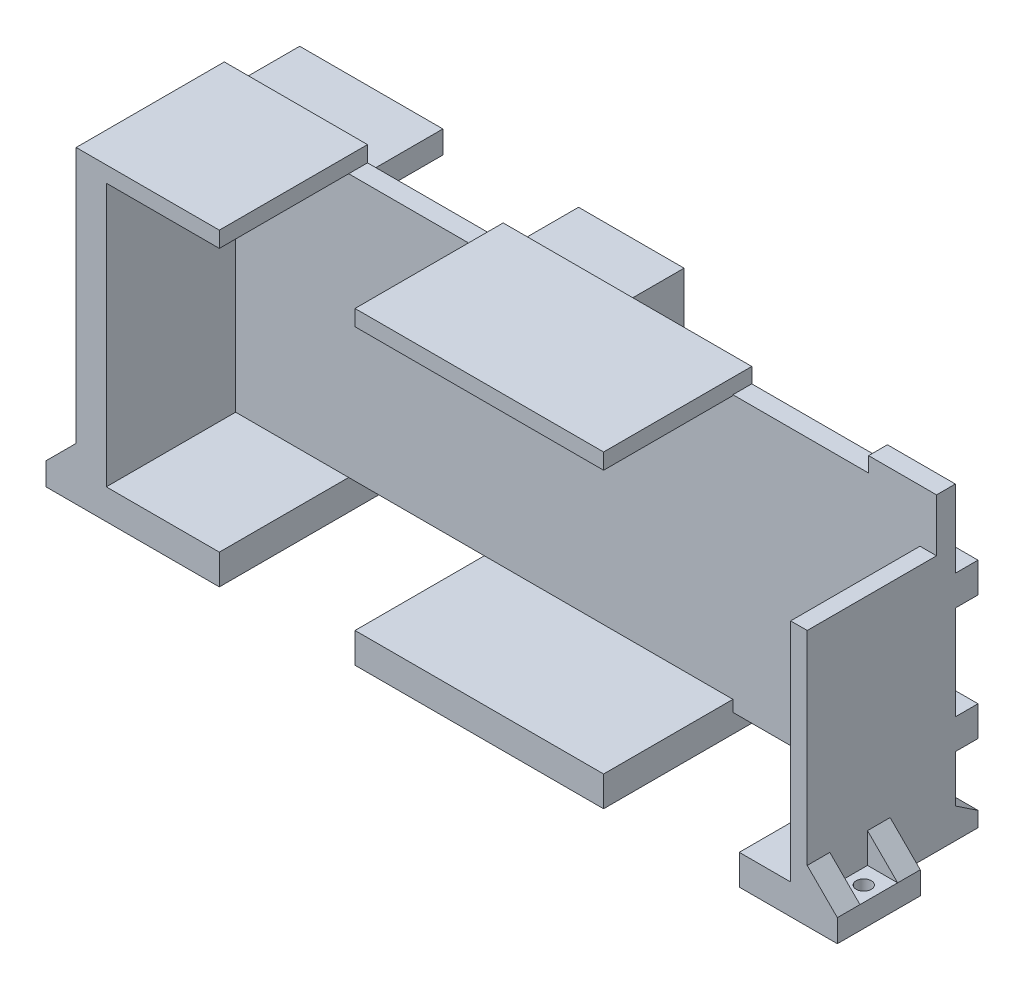
SolidWorks part; units mm, degrees
material "ABS"
ref_plane "Front Plane" through (0, 0, 0) normal (0, 0, 1) x (1, 0, 0)
ref_plane "Top Plane" through (0, 0, 0) normal (0, 1, 0) x (1, 0, 0)
ref_plane "Right Plane" through (0, 0, 0) normal (1, 0, 0) x (0, 0, -1)
sketch "Sketch1" plane through (0, 0, 0) normal (0, 0, 1) x (1, 0, 0)
  line L1 (29.337, -20.193) -> (-29.337, -20.193)
  line L2 (29.337, -20.193) -> (29.337, 20.193)
  line L3 (29.337, 20.193) -> (-29.337, 20.193)
  line L4 (-29.337, -20.193) -> (-29.337, 20.193)
  line L5 (29.337, -20.193) -> (-29.337, 20.193) construction
  line L6 (29.337, 20.193) -> (-29.337, -20.193) construction
  line L7 (32.385, 24.003) -> (-32.385, 24.003)
  line L8 (32.385, 24.003) -> (32.385, -24.003)
  line L9 (32.385, -24.003) -> (-32.385, -24.003)
  line L10 (-32.385, 24.003) -> (-32.385, -24.003)
  line L11 (32.385, 24.003) -> (-32.385, -24.003) construction
  line L12 (32.385, -24.003) -> (-32.385, 24.003) construction
  point P0 (0, 0)
  point P6 (0, 0)
  dimension "D1" = 40.386
  dimension "D2" = 58.674
  dimension "D3" = 3.048
  dimension "D4" = 3.81
  dimension "D5" = 3.81
extrude "Boss-Extrude1" add sketch "Sketch1" along normal blind 12.7
sketch "Sketch3" plane through (0, 0, 12.7) normal (0, 0, 1) x (1, 0, 0)
  line L0 (79.354, -24.003) -> (79.354, -20.828)
  line L1 (-32.385, -24.003) -> (56.494, -24.003)
  line L2 (-32.385, -24.003) -> (-32.385, 28.067)
  line L3 (-32.385, 28.067) -> (56.494, 28.067)
  line L4 (90.805, -24.003) -> (90.805, 28.067)
  line L5 (79.354, -20.828) -> (56.494, -20.828)
  line L6 (56.494, -20.828) -> (56.494, -24.003)
  line L7 (79.354, -24.003) -> (90.805, -24.003)
  line L8 (79.354, 28.067) -> (79.354, 25.527)
  line L9 (79.354, 25.527) -> (56.494, 25.527)
  line L10 (56.494, 25.527) -> (56.494, 28.067)
  line L11 (79.354, 28.067) -> (90.805, 28.067)
  dimension "D1" = 123.19
  dimension "D2" = 52.07
  dimension "D3" = 3.175
  dimension "D4" = 22.86
  dimension "D5" = 11.451
  dimension "D6" = 22.86
  dimension "D7" = 2.54
extrude "Boss-Extrude2" add sketch "Sketch3" along normal blind 3.175
sketch "Sketch5" plane through (0, 0, 15.875) normal (0, 0, 1) x (1, 0, 0)
  line L0 (-32.385, 28.067) -> (-32.385, -24.003)
  line L1 (-32.385, -24.003) -> (56.494, -24.003)
  line L2 (56.494, -24.003) -> (56.494, -18.923)
  line L3 (56.494, -18.923) -> (79.354, -18.923)
  line L4 (79.354, -18.923) -> (79.354, -24.003)
  line L5 (79.354, -24.003) -> (90.805, -24.003)
  line L6 (90.805, -24.003) -> (90.805, 19.177)
  line L7 (90.805, 28.067) -> (79.354, 28.067) construction
  line L9 (88.011, -18.923) -> (79.354, -18.923)
  line L10 (56.494, 25.4) -> (56.494, 28.067)
  line L11 (56.494, 28.067) -> (-32.385, 28.067)
  line L12 (-27.305, 25.4) -> (-27.305, -18.923)
  line L13 (-27.305, -18.923) -> (56.494, -18.923)
  line L14 (79.354, -24.003) -> (79.354, -18.923)
  line L15 (88.011, -18.923) -> (88.011, 19.177)
  line L17 (56.494, 25.4) -> (-27.305, 25.4)
  line L18 (88.011, 19.177) -> (90.805, 19.177)
  line M7 (-32.385, 28.067) -> (-32.385, -24.003)
  line M8 (-32.385, -24.003) -> (56.494, -24.003)
  line M9 (56.494, -24.003) -> (56.494, -20.828)
  line M11 (79.354, -20.828) -> (79.354, -24.003)
  line M12 (79.354, -24.003) -> (90.805, -24.003)
  line M13 (90.805, -24.003) -> (90.805, 28.067)
  line M17 (56.494, 25.527) -> (56.494, 28.067)
  line M18 (56.494, 28.067) -> (-32.385, 28.067)
  dimension "D1" = 5.08
  dimension "D2" = 2.794
  dimension "D3" = 2.667
  dimension "D4" = 5.08
  dimension "D5" = 8.89
extrude "Boss-Extrude3" add sketch "Sketch5" along normal blind 21.7932 contours L17 L10 L13 L12 M17 M18 M7 M8 M9 | L18 L15 L9 M11 M12 M13
sketch "Sketch6" plane through (0, 0, 37.6682) normal (0, 0, 1) x (1, 0, 0)
  line L1 (-8.255, 28.067) -> (14.605, 28.067)
  line L2 (-8.255, 28.067) -> (-8.255, 25.4)
  line L3 (-8.255, 25.4) -> (14.605, 25.4)
  line L4 (14.605, 28.067) -> (14.605, 25.4)
  line L9 (-8.255, -24.003) -> (-8.255, -18.923)
  line L12 (-8.255, -18.923) -> (14.605, -18.923)
  line L13 (14.605, -18.923) -> (14.605, -24.003)
  line L14 (14.605, -24.003) -> (-8.255, -24.003)
  line L17 (56.494, 28.067) -> (-32.385, 28.067) construction
  line L18 (-32.385, 28.067) -> (-32.385, -24.003) construction
  line L20 (-32.385, -24.003) -> (56.494, -24.003) construction
  line L24 (56.494, 25.4) -> (-27.305, 25.4) construction
  line L25 (-27.305, -18.923) -> (56.494, -18.923) construction
  dimension "D1" = 22.86
  dimension "D2" = 24.13
extrude "Cut-Extrude1" cut sketch "Sketch6" against normal through all
sketch "Sketch7" plane through (0, 0, 0) normal (0, 0, -1) x (-1, 0, 0)
  line L0 (-32.385, 24.003) -> (32.385, 24.003) construction
  line L1 (-14.605, 24.003) -> (8.255, 24.003)
  line L2 (-14.605, 24.003) -> (-14.605, 20.193)
  line L3 (-14.605, 20.193) -> (8.255, 20.193)
  line L4 (8.255, 24.003) -> (8.255, 20.193)
  line L5 (-29.337, 20.193) -> (29.337, 20.193) construction
  line L6 (29.337, -20.193) -> (8.255, -20.193) construction
  line L7 (-14.605, -20.193) -> (8.255, -20.193)
  line L8 (-14.605, -20.193) -> (-14.605, -21.336)
  line L9 (-14.605, -21.336) -> (8.255, -21.336)
  line L10 (8.255, -20.193) -> (8.255, -21.336)
  line L11 (-14.605, -20.193) -> (-14.605, -24.003) construction
  line L14 (8.255, 28.067) -> (8.255, 24.003) construction
  line L15 (-14.605, 24.003) -> (-14.605, 28.067) construction
extrude "Cut-Extrude2" cut sketch "Sketch7" against normal blind 12.7
sketch "Sketch10" plane through (-32.385, 0, 0) normal (-1, 0, 0) x (0, 0, 1)
  line L0 (30.6832, -24.003) -> (30.6832, -21.2771) construction
  line L1 (37.6682, -24.003) -> (0, -24.003) construction
  line L2 (37.6682, 28.067) -> (37.6682, -24.003) construction
  line L3 (23.6982, -24.003) -> (37.6682, -24.003)
  line L4 (23.6982, -24.003) -> (23.6982, -20.193)
  line L5 (23.6982, -20.193) -> (37.6682, -20.193)
  line L6 (37.6682, -24.003) -> (37.6682, -20.193)
  dimension "D1" = 13.97
  dimension "D2" = 3.81
extrude "Boss-Extrude4" add sketch "Sketch10" along normal blind 5.08
sketch "Sketch11" plane through (0, 0, 37.6682) normal (0, 0, 1) x (1, 0, 0)
  line L0 (-37.465, -20.193) -> (-32.385, -20.193)
  line L1 (-32.385, -20.193) -> (-32.385, -15.113)
  line L3 (-32.385, -15.113) -> (-37.465, -20.193)
  line L4 (-32.385, 28.067) -> (-32.385, -24.003) construction
  dimension "D1" = 5.08
  dimension "D2" = 5.08
extrude "Boss-Extrude5" add sketch "Sketch11" against normal blind 3.81
sketch "Sketch12" plane through (0, -20.193, 0) normal (0, 1, 0) x (1, 0, 0)
  line L0 (-34.925, -23.6982) -> (-34.925, -37.6682) construction
  line L1 (-37.465, -23.6982) -> (-32.385, -23.6982) construction
  line L2 (-32.385, -37.6682) -> (-37.465, -37.6682) construction
  line L3 (-37.465, -30.6832) -> (-32.385, -30.6832) construction
  line L4 (-37.465, -33.8582) -> (-37.465, -23.6982) construction
  line L5 (-32.385, -37.6682) -> (-32.385, -12.7) construction
  circle A0 centre (-34.925, -30.6832) radius 1.27
  dimension "D1" = 2.54
extrude "Cut-Extrude3" cut sketch "Sketch12" against normal through all
sketch "Sketch13" plane through (0, 0, 23.6982) normal (0, 0, -1) x (-1, 0, 0)
  line L0 (32.385, -15.113) -> (32.385, -20.193)
  line L1 (32.385, -20.193) -> (37.465, -20.193)
  line L2 (37.465, -20.193) -> (32.385, -15.113)
extrude "Boss-Extrude7" add sketch "Sketch13" against normal blind 3.81
sketch "Sketch14" plane through (90.805, 0, 0) normal (1, 0, 0) x (0, 0, -1)
  line L0 (-37.6682, -24.003) -> (-37.6682, 19.177) construction
  line L1 (-37.6682, -24.003) -> (-12.7, -24.003) construction
  line L3 (-37.6682, -24.003) -> (-23.6982, -24.003)
  line L4 (-37.6682, -24.003) -> (-37.6682, -20.193)
  line L5 (-37.6682, -20.193) -> (-23.6982, -20.193)
  line L6 (-23.6982, -24.003) -> (-23.6982, -20.193)
  dimension "D1" = 13.97
  dimension "D2" = 3.81
extrude "Boss-Extrude8" add sketch "Sketch14" along normal blind 5.08
sketch "Sketch15" plane through (0, -20.193, 0) normal (0, 1, 0) x (1, 0, 0)
  line L0 (90.805, -30.6832) -> (95.885, -30.6832) construction
  line L1 (90.805, -23.6982) -> (90.805, -37.6682) construction
  line L2 (95.885, -23.6982) -> (95.885, -37.6682) construction
  line L3 (93.345, -37.6682) -> (93.345, -23.6982) construction
  line L4 (95.885, -37.6682) -> (90.805, -37.6682) construction
  line L5 (95.885, -23.6982) -> (90.805, -23.6982) construction
  circle A0 centre (93.345, -30.6832) radius 1.27
  circle A1 centre (-34.925, -30.6832) radius 1.27 construction
  dimension "D1" = 2.54
  dimension "D2" = 0
  dimension "D3" = 128.27
extrude "Cut-Extrude4" cut sketch "Sketch15" against normal through all
sketch "Sketch17" plane through (0, 0, 37.6682) normal (0, 0, 1) x (1, 0, 0)
  line L0 (95.885, -20.193) -> (90.805, -20.193)
  line L1 (90.805, -20.193) -> (90.805, -15.113)
  line L3 (90.805, -20.193) -> (90.805, 19.177) construction
  line L4 (90.805, -15.113) -> (95.885, -20.193)
extrude "Boss-Extrude9" add sketch "Sketch17" against normal blind 3.81
sketch "Sketch18" plane through (0, 0, 23.6982) normal (0, 0, -1) x (-1, 0, 0)
  line L0 (-95.885, -20.193) -> (-90.805, -20.193)
  line L1 (-90.805, -20.193) -> (-90.805, -15.113)
  line L2 (-90.805, -15.113) -> (-95.885, -20.193)
extrude "Boss-Extrude10" add sketch "Sketch18" against normal blind 3.81
sketch "Sketch19" plane through (0, 28.067, 0) normal (0, 1, 0) x (1, 0, 0)
  line L1 (90.805, -12.7) -> (86.995, -12.7)
  line L2 (90.805, -12.7) -> (90.805, -8.89)
  line L3 (90.805, -8.89) -> (86.995, -8.89)
  line L4 (86.995, -12.7) -> (86.995, -8.89)
  dimension "D1" = 3.81
  dimension "D2" = 3.81
extrude "Boss-Extrude11" [suppressed] add sketch "Sketch19" against normal up to surface (52.07 mm away)
sketch "Sketch20" [suppressed] plane through (0, 0, 12.7) normal (0, 0, -1) x (-1, 0, 0)
  line L0 (-67.924, -20.828) -> (-67.924, 25.527) construction
  line L1 (-56.494, -20.828) -> (-79.354, -20.828) construction
  line L2 (-79.354, 25.527) -> (-56.494, 25.527) construction
  line L3 (-32.385, -24.003) -> (-32.385, 24.003) construction
  line L4 (-32.385, -8.128) -> (-86.995, -8.128)
  line L5 (-32.385, -8.128) -> (-32.385, -11.938)
  line L6 (-32.385, -11.938) -> (-86.995, -11.938)
  line L7 (-86.995, -8.128) -> (-86.995, -11.938)
  line L8 (-86.995, -24.003) -> (-86.995, 28.067) construction
  line L9 (-86.995, -24.003) -> (-86.995, 28.067) construction
  line L10 (-32.385, 16.637) -> (-86.995, 16.637)
  line L11 (-32.385, 16.637) -> (-32.385, 12.827)
  line L12 (-32.385, 12.827) -> (-86.995, 12.827)
  line L13 (-86.995, 16.637) -> (-86.995, 12.827)
  dimension "D1" = 54.61
  dimension "D2" = 3.81
  dimension "D3" = 3.81
  dimension "D4" = 54.61
  dimension "D5" = 8.89
  dimension "D6" = 8.89
extrude "Boss-Extrude12" [suppressed] add sketch "Sketch20" along normal blind 3.81
sketch "Sketch21" plane through (0, 0, 12.7) normal (0, 0, -1) x (-1, 0, 0)
  line L0 (-32.385, -24.003) -> (-32.385, 24.003) construction
  line L1 (-32.385, 15.0495) -> (-90.805, 15.0495)
  line L2 (-32.385, 15.0495) -> (-32.385, 9.9695)
  line L3 (-32.385, 9.9695) -> (-90.805, 9.9695)
  line L4 (-90.805, 15.0495) -> (-90.805, 9.9695)
  line L5 (-90.805, -24.003) -> (-90.805, 28.067) construction
  line L6 (-56.494, 28.067) -> (-14.605, 28.067) construction
  line L7 (-32.385, -5.9055) -> (-90.805, -5.9055)
  line L8 (-32.385, -5.9055) -> (-32.385, -10.9855)
  line L9 (-32.385, -10.9855) -> (-90.805, -10.9855)
  line L10 (-90.805, -5.9055) -> (-90.805, -10.9855)
  line L11 (-32.385, -24.003) -> (-56.494, -24.003) construction
  line L12 (-79.354, -20.828) -> (-79.354, -24.003) construction
  line L13 (-56.494, -24.003) -> (-32.385, -24.003)
  line L14 (-56.494, -24.003) -> (-56.494, -21.463)
  line L15 (-56.494, -21.463) -> (-32.385, -21.463)
  line L16 (-32.385, -24.003) -> (-32.385, -21.463)
  line L17 (-90.805, -24.003) -> (-79.354, -24.003)
  line L18 (-90.805, -24.003) -> (-90.805, -21.463)
  line L19 (-90.805, -21.463) -> (-79.354, -21.463)
  line L20 (-79.354, -24.003) -> (-79.354, -21.463)
  dimension "D1" = 58.42
  dimension "D2" = 5.08
  dimension "D3" = 58.42
  dimension "D4" = 5.08
  dimension "D5" = 13.0175
  dimension "D6" = 13.0175
  dimension "D7" = 2.54
  dimension "D8" = 2.54
extrude "Boss-Extrude13" add sketch "Sketch21" along normal blind 3.81
sketch "Sketch22" plane through (56.494, 0, 0) normal (1, 0, 0) x (0, 0, -1)
  line L0 (-8.89, -21.463) -> (-12.7, -21.463)
  line L1 (-12.7, -21.463) -> (-12.7, -18.923)
  line L2 (-12.7, -18.923) -> (-8.89, -21.463)
  dimension "D1" = 2.54
  dimension "D2" = 3.81
extrude "Boss-Extrude14" add sketch "Sketch22" against normal up to surface (24.109 mm away) up to face at (32.385, -3.1659, 9.5704)
sketch "Sketch23" plane through (90.805, 0, 0) normal (1, 0, 0) x (0, 0, -1)
  line L0 (-8.89, -21.463) -> (-12.7, -21.463)
  line L1 (-12.7, -21.463) -> (-12.7, -18.923)
  line L2 (-12.7, -21.463) -> (-12.7, -10.9855) construction
  line L3 (-12.7, -18.923) -> (-8.89, -21.463)
  dimension "D1" = 2.54
extrude "Boss-Extrude15" add sketch "Sketch23" against normal up to surface (11.451 mm away) up to face at (79.354, -21.3042, 18.7833)
